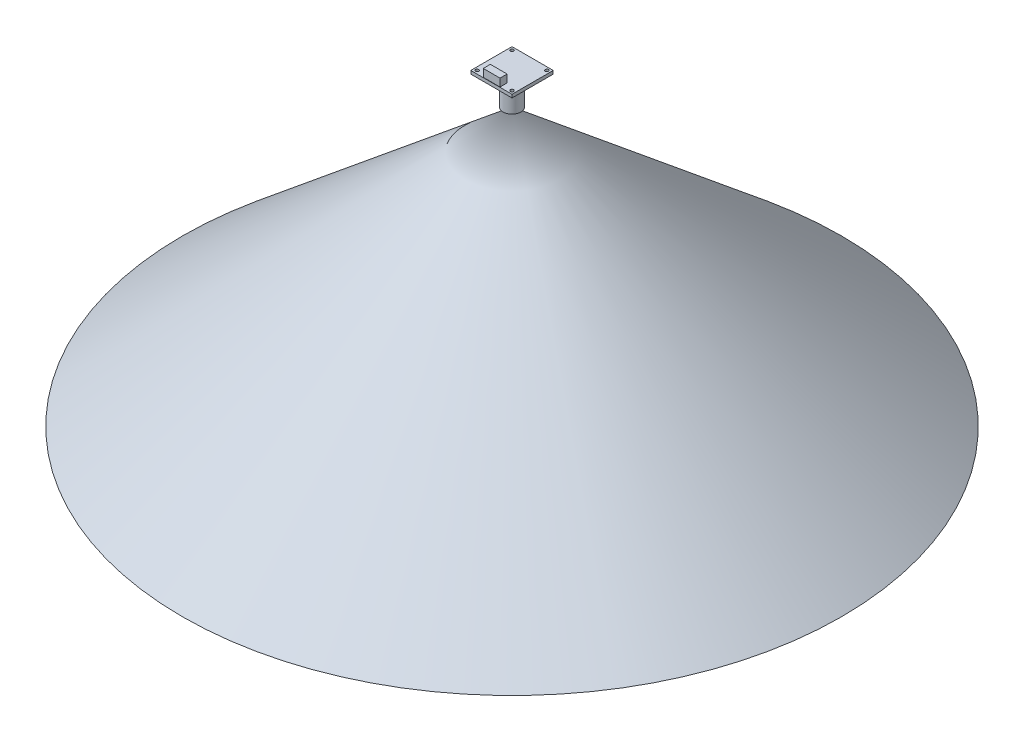
SolidWorks part; units mm, degrees
ref_plane "前视基准面" through (0, 0, 0) normal (0, 0, 1) x (1, 0, 0)
ref_plane "上视基准面" through (0, 0, 0) normal (0, 1, 0) x (1, 0, 0)
ref_plane "右视基准面" through (0, 0, 0) normal (1, 0, 0) x (0, 0, -1)
other "Configuration Table"
sketch "草图1" plane through (0, 0, 0) normal (0, 1, 0) x (1, 0, 0)
  line L0 (0, 0) -> (0, 16) construction
  line L1 (-16, 16) -> (16, 16)
  line L2 (-16, 16) -> (-16, -16)
  line L3 (-16, -16) -> (16, -16)
  line L4 (16, 16) -> (16, -16)
  line L5 (-16, 16) -> (16, -16) construction
  line L6 (-16, -16) -> (16, 16) construction
  line L7 (0, 0) -> (-28.9334, 0) construction
  circle A0 centre (-13.5, 13.5) radius 1.25
  circle A1 centre (13.5, 13.5) radius 1.25
  circle A2 centre (13.5, -13.5) radius 1.25
  circle A3 centre (-13.5, -13.5) radius 1.25
  point P0 (0, 0)
  dimension "D3" = 2.5
  dimension "D4" = 27
  dimension "D1" = 32
  dimension "D2" = 32
extrude "凸台-拉伸1" add sketch "草图1" along normal blind 2.5
sketch "草图2" plane through (0, 2.5, 0) normal (0, 1, 0) x (1, 0, 0)
  line L0 (0, 0) -> (0, -16) construction
  line L1 (-16, -16) -> (16, -16) construction
  line L3 (-6.5, -15.8) -> (6.5, -15.8)
  line L4 (-6.5, -15.8) -> (-6.5, -10.3)
  line L5 (-6.5, -10.3) -> (6.5, -10.3)
  line L6 (6.5, -15.8) -> (6.5, -10.3)
  line L7 (-6.5, -15.8) -> (6.5, -10.3) construction
  line L8 (-6.5, -10.3) -> (6.5, -15.8) construction
  point P5 (0, -13.05)
  dimension "D1" = 13
  dimension "D2" = 5.5
  dimension "D3" = 0.2
extrude "凸台-拉伸2" add sketch "草图2" along normal blind 6 separate body
sketch "草图3" plane through (0, 0, 0) normal (0, -1, 0) x (1, 0, 0)
  circle A0 centre (0, 0) radius 6.9
  dimension "D1" = 13.8
extrude "凸台-拉伸3" add sketch "草图3" along normal blind 22 separate body
ref_axis "基准轴1" through (0, 10.025, 0) along (0, -1, 0)
sketch "草图5" plane through (0, 0, 0) normal (0, 0, 1) x (1, 0, 0)
  line L0 (0, -22) -> (255.8003, -236.6419)
  line L1 (-6.9, -22) -> (6.9, -22) construction
  line L2 (0, -22) -> (0, -236.6419)
  line L3 (0, 10.025) -> (0, -39.9931) construction
  line L4 (0, -236.6419) -> (255.8003, -236.6419)
  dimension "D1" = 50
revolve "旋转1" add sketch "草图5" angle 360 about axis through (0, 10.025, 0) along (0, -1, 0)
